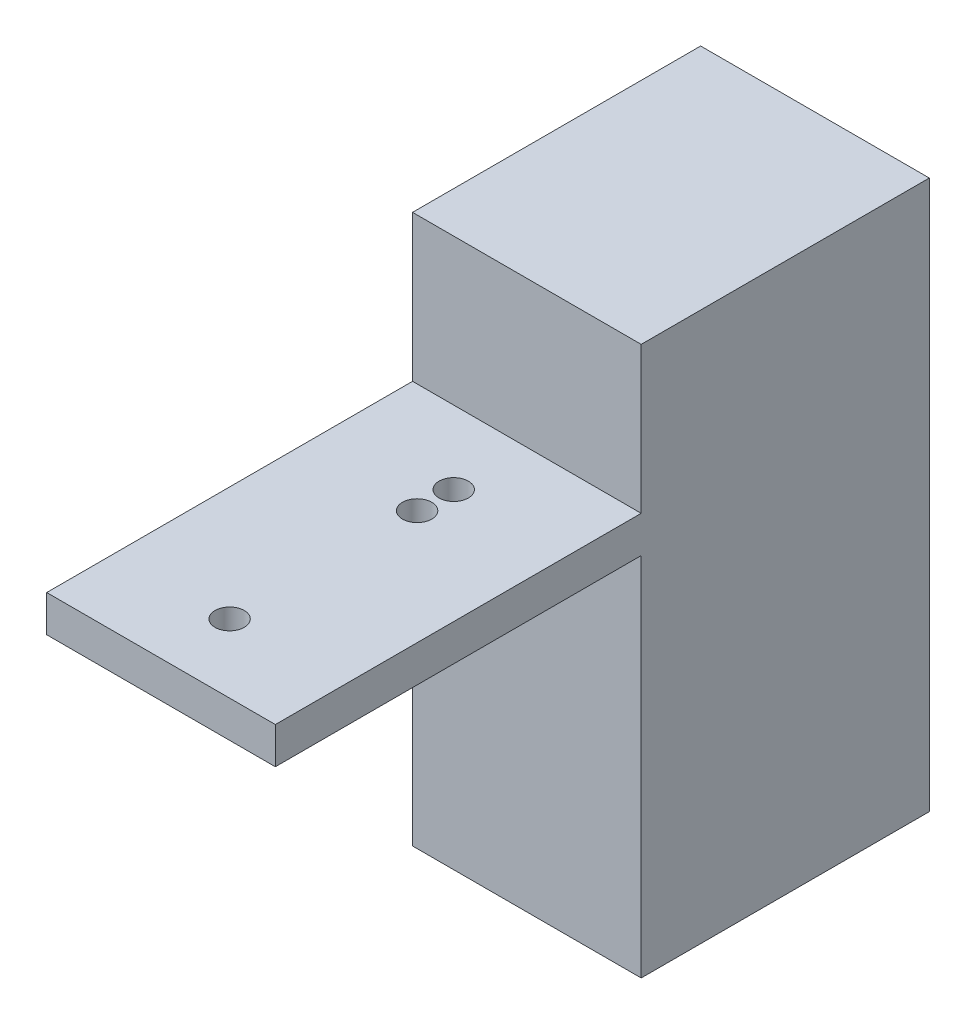
SolidWorks part; units mm, degrees
ref_plane "Front Plane" through (0, 0, 0) normal (0, 0, 1) x (1, 0, 0)
ref_plane "Top Plane" through (0, 0, 0) normal (0, 1, 0) x (1, 0, 0)
ref_plane "Right Plane" through (0, 0, 0) normal (1, 0, 0) x (0, 0, -1)
sketch "Sketch1" plane through (0, 0, 0) normal (1, 0, 0) x (0, 0, -1)
  line L0 (-40, 30) -> (0, 30)
  line L1 (-40, 30) -> (-40, 34)
  line L2 (-40, 34) -> (0, 34)
  line L3 (0, 34) -> (0, 50)
  line L4 (0, 50) -> (31.5, 50)
  line L5 (31.5, 50) -> (31.5, 40)
  line L6 (31.5, 40) -> (4, 40)
  line L7 (4, 40) -> (4, 0)
  line L8 (4, 0) -> (31.5, 0)
  line L9 (31.5, 0) -> (31.5, -10)
  line L10 (31.5, -10) -> (0, -10)
  line L11 (0, -10) -> (0, 30)
  line L12 (4, 30) -> (31.5, 30) construction
  line L13 (4, 0) -> (0, 0) construction
  line L14 (31.5, 40) -> (31.5, 0)
  point P15 (0, 0)
  dimension "D1" = 40
  dimension "D2" = 40
  dimension "D3" = 27.5
  dimension "D4" = 10
  dimension "D5" = 60
  dimension "D6" = 4
extrude "Boss-Extrude1" add sketch "Sketch1" along normal mid plane 25 contours L14 L6 L7 L8 | L11 L10 L9 L8 L7 L6 L5 L4 L3 L2 L1 L0
sketch "Sketch2" plane through (0, 0, -31.5) normal (0, 0, -1) x (-1, 0, 0)
  line L0 (10.015, 40.015) -> (10.015, 50) construction
  line L1 (10.015, -0.015) -> (-10.015, -0.015)
  line L2 (10.015, -0.015) -> (10.015, 40.015)
  line L3 (10.015, 40.015) -> (-10.015, 40.015)
  line L4 (-10.015, -0.015) -> (-10.015, 40.015)
  line L5 (10.015, -0.015) -> (-10.015, 40.015) construction
  line L6 (10.015, 40.015) -> (-10.015, -0.015) construction
  line L7 (-12.5, 50) -> (12.5, 50) construction
  line L8 (10.015, -0.015) -> (10.015, -10) construction
  line L9 (-12.5, -10) -> (12.5, -10) construction
  line L11 (5, -4) -> (-5, -4)
  line L12 (5, -4) -> (5, 44)
  line L13 (5, 44) -> (-5, 44)
  line L14 (-5, -4) -> (-5, 44)
  line L15 (5, -4) -> (-5, 44) construction
  line L16 (5, 44) -> (-5, -4) construction
  point P0 (0, 20)
  point P16 (0, 20)
  dimension "D1" = 40.03
  dimension "D2" = 20.03
  dimension "D3" = 48
  dimension "D4" = 10
extrude "Cut-Extrude1" cut sketch "Sketch2" against normal mid plane 27.53 contours L12 L1 L2 L3 | L14 L1 L12 L3 | L1 L14 L3 L4
sketch "Sketch6" plane through (0, 0, -31.5) normal (0, 0, -1) x (-1, 0, 0)
  circle A0 centre (-5, 44) radius 3.25
  circle A1 centre (5, 44) radius 3.25
  circle A2 centre (5, -4) radius 3.25
  circle A3 centre (-5, -4) radius 3.25
  dimension "D1" = 6.5
extrude "Cut-Extrude2" cut sketch "Sketch6" against normal blind 12 contours A0
sketch "Sketch7" plane through (0, 34, 0) normal (0, 1, 0) x (1, 0, 0)
  line L0 (0, -8) -> (0, -12)
  line L1 (0, -12) -> (0, -32.5)
  line L3 (12.5, -40) -> (-12.5, -40) construction
  circle A4 centre (0, -32.5) radius 1.6
  circle A5 centre (0, -12) radius 1.6
  circle A6 centre (0, -8) radius 1.6
  dimension "D1" = 20.5
  dimension "D3" = 7.5
  dimension "D4" = 3.2
  dimension "D2" = 4
extrude "Cut-Extrude3" cut sketch "Sketch7" against normal through all
